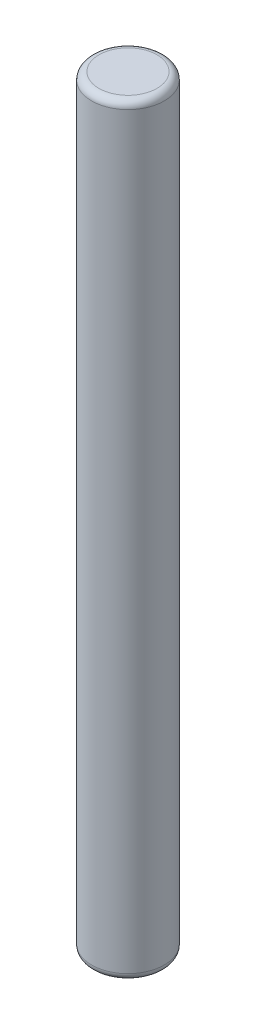
SolidWorks part; units mm, degrees
ref_plane "Front Plane" through (0, 0, 0) normal (0, 0, 1) x (1, 0, 0)
ref_plane "Top Plane" through (0, 0, 0) normal (0, 1, 0) x (1, 0, 0)
ref_plane "Right Plane" through (0, 0, 0) normal (1, 0, 0) x (0, 0, -1)
sketch "Sketch1" plane through (0, 0, 0) normal (0, 1, 0) x (1, 0, 0)
  circle A0 centre (0, 0) radius 0.5
  dimension "D1" = 1
extrude "Boss-Extrude1" add sketch "Sketch1" along normal blind 10 and the other way blind 0.5
fillet "Fillet1" radius 0.1 2 edges at (0, -0.5, 0.5) (0, 10, 0.5)
